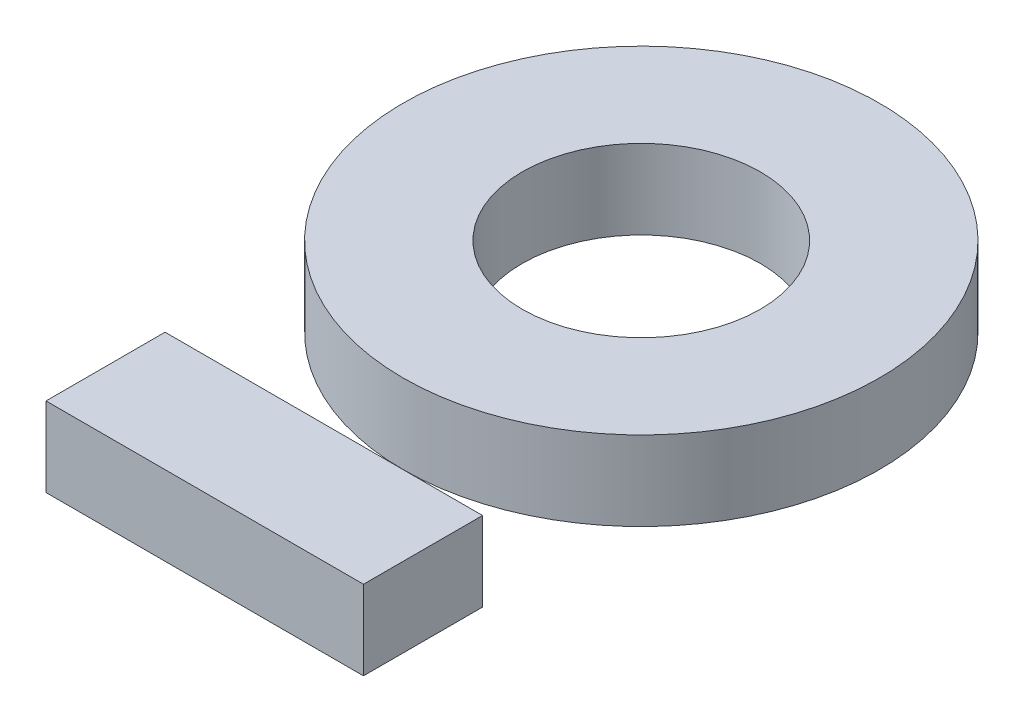
SolidWorks part; units mm, degrees
ref_plane "Front Plane" through (0, 0, 0) normal (0, 0, 1) x (1, 0, 0)
ref_plane "Top Plane" through (0, 0, 0) normal (0, 1, 0) x (1, 0, 0)
ref_plane "Right Plane" through (0, 0, 0) normal (1, 0, 0) x (0, 0, -1)
sketch "Sketch1" plane through (0, 0, 0) normal (0, 1, 0) x (1, 0, 0)
  line L1 (-12.7, -25.4) -> (12.7, -25.4)
  line L2 (-12.7, -25.4) -> (-12.7, -34.925)
  line L3 (-12.7, -34.925) -> (12.7, -34.925)
  line L4 (12.7, -25.4) -> (12.7, -34.925)
  circle A0 centre (0, 0) radius 9.525
  circle A1 centre (0, 0) radius 19.05
  point P8 (0, -25.4)
  dimension "D1" = 38.1
  dimension "D2" = 19.05
  dimension "D3" = 9.525
  dimension "D4" = 25.4
  dimension "D5" = 25.4
extrude "Boss-Extrude1" add sketch "Sketch1" along normal blind 6.35
